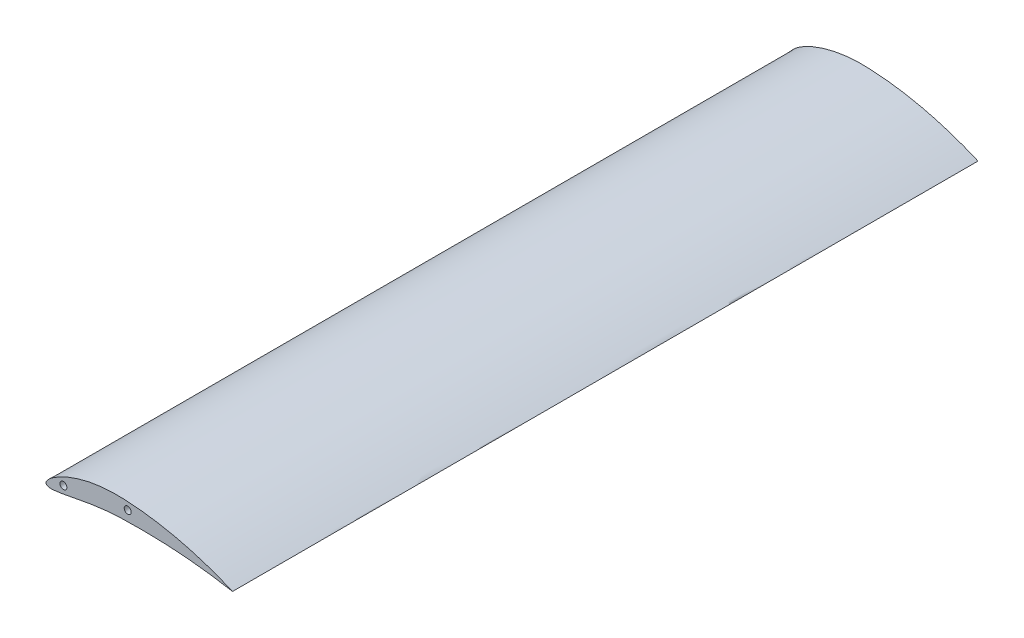
SolidWorks part; units mm, degrees
material "Thornel Mat VMA"
ref_plane "Front Plane" through (0, 0, 0) normal (0, 0, 1) x (1, 0, 0)
ref_plane "Top Plane" through (0, 0, 0) normal (0, 1, 0) x (1, 0, 0)
ref_plane "Right Plane" through (0, 0, 0) normal (1, 0, 0) x (0, 0, -1)
curve "Curve1"
  spline degree 3 poles (253.4485, 0.1124, 0) (254.1344, -0.0403, 0) (253.4775, 0.2094, 0) (252.9495, 0.4611, 0) (251.6343, 1.0083, 0) (250.0027, 1.7035, 0) (247.8318, 2.6061, 0) (245.222, 3.6772, 0) (242.1466, 4.9135, 0) (238.6277, 6.2968, 0) (234.6723, 7.8101, 0) (230.2949, 9.4358, 0) (225.5097, 11.1539, 0) (220.3329, 12.9444, 0) (214.7822, 14.7852, 0) (208.8774, 16.6562, 0) (202.6392, 18.5351, 0) (196.0902, 20.401, 0) (189.2544, 22.2326, 0) (182.1573, 24.0099, 0) (174.8257, 25.7128, 0) (167.2876, 27.3233, 0) (159.5723, 28.8237, 0) (151.7102, 30.1982, 0) (143.7328, 31.4322, 0) (135.6725, 32.5129, 0) (127.5623, 33.4286, 0) (119.4362, 34.1722, 0) (111.3283, 34.7326, 0) (103.2114, 35.1211, 0) (95.0995, 35.2824, 0) (87.0296, 35.0756, 0) (79.1065, 34.5435, 0) (71.3864, 33.6939, 0) (63.9086, 32.5516, 0) (56.7107, 31.1413, 0) (49.828, 29.4941, 0) (43.2936, 27.6424, 0) (37.1382, 25.6216, 0) (31.3885, 23.4707, 0) (26.0698, 21.2262, 0) (21.2028, 18.928, 0) (16.8058, 16.6139, 0) (12.8942, 14.3201, 0) (9.479, 12.0827, 0) (6.5699, 9.9326, 0) (4.1722, 7.8987, 0) (2.2877, 6.0051, 0) (0.9134, 4.2681, 0) (0.0444, 2.693, 0) (-0.3184, 1.2547, 0) (-0.0942, -0.0424, 0) (0.7257, -1.0686, 0) (2.0258, -1.7597, 0) (3.7478, -2.1864, 0) (5.9052, -2.3819, 0) (8.4963, -2.362, 0) (11.5132, -2.1403, 0) (14.9421, -1.7327, 0) (18.7667, -1.158, 0) (22.969, -0.4369, 0) (27.5301, 0.4071, 0) (32.4305, 1.3497, 0) (37.6504, 2.3649, 0) (43.1697, 3.4266, 0) (48.969, 4.507, 0) (55.0285, 5.5791, 0) (61.3291, 6.6157, 0) (67.8521, 7.5898, 0) (74.5787, 8.4752, 0) (81.4905, 9.2487, 0) (88.5689, 9.8833, 0) (95.8108, 10.3684, 0) (103.2588, 10.6511, 0) (110.8834, 10.8473, 0) (118.6426, 10.9921, 0) (126.4465, 11.0627, 0) (134.266, 11.0574, 0) (142.0724, 10.9714, 0) (149.836, 10.8029, 0) (157.5272, 10.5515, 0) (165.1159, 10.2196, 0) (172.5722, 9.8112, 0) (179.8661, 9.3312, 0) (186.9679, 8.7873, 0) (193.8486, 8.1886, 0) (200.4792, 7.5439, 0) (206.832, 6.8648, 0) (212.8796, 6.1626, 0) (218.596, 5.4497, 0) (223.9561, 4.7376, 0) (228.9365, 4.0391, 0) (233.5145, 3.366, 0) (237.67, 2.7297, 0) (241.3824, 2.1406, 0) (244.6389, 1.6085, 0) (247.4122, 1.1449, 0) (249.7238, 0.7475, 0) (251.4697, 0.4504, 0) (252.8691, 0.191, 0) (253.4485, 0.1124, 0) (254.1344, -0.0403, 0) (253.4775, 0.2094, 0) knots -0.004489 -0.002 -0.000501 0 0.0005 0.002 0.004491 0.007963 0.0124 0.017783 0.024086 0.031283 0.039342 0.048229 0.057904 0.068328 0.079457 0.091243 0.10364 0.116598 0.130063 0.143985 0.158306 0.172972 0.187927 0.203113 0.218472 0.233945 0.249473 0.264999 0.280462 0.295804 0.311324 0.326707 0.34181 0.356583 0.370972 0.384924 0.398387 0.411307 0.423633 0.435312 0.446295 0.456535 0.465988 0.474613 0.482377 0.489253 0.495224 0.500286 0.504461 0.507812 0.510481 0.512762 0.515043 0.517702 0.521013 0.525104 0.530021 0.535772 0.542341 0.549703 0.557819 0.566648 0.576147 0.586268 0.596965 0.60819 0.619899 0.632047 0.644592 0.657497 0.670724 0.68424 0.698011 0.712098 0.726728 0.741494 0.756341 0.771219 0.786073 0.800848 0.81549 0.829943 0.844153 0.858061 0.871615 0.884758 0.897436 0.909595 0.921182 0.932145 0.942437 0.952008 0.960816 0.968817 0.975974 0.98225 0.987616 0.992043 0.995511 0.998 0.999499 1 1.0005 1.002 1.004491 periodic
sketch "Sketch1" plane through (0, 0, 0) normal (0, 0, 1) x (1, 0, 0)
  spline S0 degree 3 poles (253.4485, 0.1124) (254.1344, -0.0403) (253.4775, 0.2094) (252.9495, 0.4611) (251.6343, 1.0083) (250.0027, 1.7035) (247.8318, 2.6061) (245.222, 3.6772) (242.1466, 4.9135) (238.6277, 6.2968) (234.6723, 7.8101) (230.2949, 9.4358) (225.5097, 11.1539) (220.3329, 12.9444) (214.7822, 14.7852) (208.8774, 16.6562) (202.6392, 18.5351) (196.0902, 20.401) (189.2544, 22.2326) (182.1573, 24.0099) (174.8257, 25.7128) (167.2876, 27.3233) (159.5723, 28.8237) (151.7102, 30.1982) (143.7328, 31.4322) (135.6725, 32.5129) (127.5623, 33.4286) (119.4362, 34.1722) (111.3283, 34.7326) (103.2114, 35.1211) (95.0995, 35.2824) (87.0296, 35.0756) (79.1065, 34.5435) (71.3864, 33.6939) (63.9086, 32.5516) (56.7107, 31.1413) (49.828, 29.4941) (43.2936, 27.6424) (37.1382, 25.6216) (31.3885, 23.4707) (26.0698, 21.2262) (21.2028, 18.928) (16.8058, 16.6139) (12.8942, 14.3201) (9.479, 12.0827) (6.5699, 9.9326) (4.1722, 7.8987) (2.2877, 6.0051) (0.9134, 4.2681) (0.0444, 2.693) (-0.3184, 1.2547) (-0.0942, -0.0424) (0.7257, -1.0686) (2.0258, -1.7597) (3.7478, -2.1864) (5.9052, -2.3819) (8.4963, -2.362) (11.5132, -2.1403) (14.9421, -1.7327) (18.7667, -1.158) (22.969, -0.4369) (27.5301, 0.4071) (32.4305, 1.3497) (37.6504, 2.3649) (43.1697, 3.4266) (48.969, 4.507) (55.0285, 5.5791) (61.3291, 6.6157) (67.8521, 7.5898) (74.5787, 8.4752) (81.4905, 9.2487) (88.5689, 9.8833) (95.8108, 10.3684) (103.2588, 10.6511) (110.8834, 10.8473) (118.6426, 10.9921) (126.4465, 11.0627) (134.266, 11.0574) (142.0724, 10.9714) (149.836, 10.8029) (157.5272, 10.5515) (165.1159, 10.2196) (172.5722, 9.8112) (179.8661, 9.3312) (186.9679, 8.7873) (193.8486, 8.1886) (200.4792, 7.5439) (206.832, 6.8648) (212.8796, 6.1626) (218.596, 5.4497) (223.9561, 4.7376) (228.9365, 4.0391) (233.5145, 3.366) (237.67, 2.7297) (241.3824, 2.1406) (244.6389, 1.6085) (247.4122, 1.1449) (249.7238, 0.7475) (251.4697, 0.4504) (252.8691, 0.191) (253.4485, 0.1124) (254.1344, -0.0403) (253.4775, 0.2094) knots -0.004489 -0.002 -0.000501 0 0.0005 0.002 0.004491 0.007963 0.0124 0.017783 0.024086 0.031283 0.039342 0.048229 0.057904 0.068328 0.079457 0.091243 0.10364 0.116598 0.130063 0.143985 0.158306 0.172972 0.187927 0.203113 0.218472 0.233945 0.249473 0.264999 0.280462 0.295804 0.311324 0.326707 0.34181 0.356583 0.370972 0.384924 0.398387 0.411307 0.423633 0.435312 0.446295 0.456535 0.465988 0.474613 0.482377 0.489253 0.495224 0.500286 0.504461 0.507812 0.510481 0.512762 0.515043 0.517702 0.521013 0.525104 0.530021 0.535772 0.542341 0.549703 0.557819 0.566648 0.576147 0.586268 0.596965 0.60819 0.619899 0.632047 0.644592 0.657497 0.670724 0.68424 0.698011 0.712098 0.726728 0.741494 0.756341 0.771219 0.786073 0.800848 0.81549 0.829943 0.844153 0.858061 0.871615 0.884758 0.897436 0.909595 0.921182 0.932145 0.942437 0.952008 0.960816 0.968817 0.975974 0.98225 0.987616 0.992043 0.995511 0.998 0.999499 1 1.0005 1.002 1.004491 only from (254, 0) to (254, 0) construction
  spline S1 degree 3 poles (253.4485, 0.1124) (254.1344, -0.0403) (253.4775, 0.2094) (252.9495, 0.4611) (251.6343, 1.0083) (250.0027, 1.7035) (247.8318, 2.6061) (245.222, 3.6772) (242.1466, 4.9135) (238.6277, 6.2968) (234.6723, 7.8101) (230.2949, 9.4358) (225.5097, 11.1539) (220.3329, 12.9444) (214.7822, 14.7852) (208.8774, 16.6562) (202.6392, 18.5351) (196.0902, 20.401) (189.2544, 22.2326) (182.1573, 24.0099) (174.8257, 25.7128) (167.2876, 27.3233) (159.5723, 28.8237) (151.7102, 30.1982) (143.7328, 31.4322) (135.6725, 32.5129) (127.5623, 33.4286) (119.4362, 34.1722) (111.3283, 34.7326) (103.2114, 35.1211) (95.0995, 35.2824) (87.0296, 35.0756) (79.1065, 34.5435) (71.3864, 33.6939) (63.9086, 32.5516) (56.7107, 31.1413) (49.828, 29.4941) (43.2936, 27.6424) (37.1382, 25.6216) (31.3885, 23.4707) (26.0698, 21.2262) (21.2028, 18.928) (16.8058, 16.6139) (12.8942, 14.3201) (9.479, 12.0827) (6.5699, 9.9326) (4.1722, 7.8987) (2.2877, 6.0051) (0.9134, 4.2681) (0.0444, 2.693) (-0.3184, 1.2547) (-0.0942, -0.0424) (0.7257, -1.0686) (2.0258, -1.7597) (3.7478, -2.1864) (5.9052, -2.3819) (8.4963, -2.362) (11.5132, -2.1403) (14.9421, -1.7327) (18.7667, -1.158) (22.969, -0.4369) (27.5301, 0.4071) (32.4305, 1.3497) (37.6504, 2.3649) (43.1697, 3.4266) (48.969, 4.507) (55.0285, 5.5791) (61.3291, 6.6157) (67.8521, 7.5898) (74.5787, 8.4752) (81.4905, 9.2487) (88.5689, 9.8833) (95.8108, 10.3684) (103.2588, 10.6511) (110.8834, 10.8473) (118.6426, 10.9921) (126.4465, 11.0627) (134.266, 11.0574) (142.0724, 10.9714) (149.836, 10.8029) (157.5272, 10.5515) (165.1159, 10.2196) (172.5722, 9.8112) (179.8661, 9.3312) (186.9679, 8.7873) (193.8486, 8.1886) (200.4792, 7.5439) (206.832, 6.8648) (212.8796, 6.1626) (218.596, 5.4497) (223.9561, 4.7376) (228.9365, 4.0391) (233.5145, 3.366) (237.67, 2.7297) (241.3824, 2.1406) (244.6389, 1.6085) (247.4122, 1.1449) (249.7238, 0.7475) (251.4697, 0.4504) (252.8691, 0.191) (253.4485, 0.1124) (254.1344, -0.0403) (253.4775, 0.2094) knots -0.004489 -0.002 -0.000501 0 0.0005 0.002 0.004491 0.007963 0.0124 0.017783 0.024086 0.031283 0.039342 0.048229 0.057904 0.068328 0.079457 0.091243 0.10364 0.116598 0.130063 0.143985 0.158306 0.172972 0.187927 0.203113 0.218472 0.233945 0.249473 0.264999 0.280462 0.295804 0.311324 0.326707 0.34181 0.356583 0.370972 0.384924 0.398387 0.411307 0.423633 0.435312 0.446295 0.456535 0.465988 0.474613 0.482377 0.489253 0.495224 0.500286 0.504461 0.507812 0.510481 0.512762 0.515043 0.517702 0.521013 0.525104 0.530021 0.535772 0.542341 0.549703 0.557819 0.566648 0.576147 0.586268 0.596965 0.60819 0.619899 0.632047 0.644592 0.657497 0.670724 0.68424 0.698011 0.712098 0.726728 0.741494 0.756341 0.771219 0.786073 0.800848 0.81549 0.829943 0.844153 0.858061 0.871615 0.884758 0.897436 0.909595 0.921182 0.932145 0.942437 0.952008 0.960816 0.968817 0.975974 0.98225 0.987616 0.992043 0.995511 0.998 0.999499 1 1.0005 1.002 1.004491 only from (254, 0) to (254, 0)
extrude "Boss-Extrude1" add sketch "Sketch1" along normal mid plane 1016
sketch "Sketch3" plane through (0, 0, -508) normal (0, 0, -1) x (-1, 0, 0)
  line L0 (-111.1224, 24.5559) -> (-23.4523, 9.8195) construction
  line L1 (-23.4523, 9.8195) -> (-23.4523, 19.9795) construction
  line L2 (-23.4523, 9.8195) -> (-23.4523, -0.3405) construction
  line L3 (-111.1224, 24.5559) -> (-111.1224, 34.7159) construction
  circle A0 centre (-23.4523, 9.8195) radius 4.7625
  circle A1 centre (-111.1224, 24.5559) radius 4.7625
  spline S1 degree 3 poles (-253.4775, 0.2094) (-254.1344, -0.0403) (-253.4485, 0.1124) (-252.8691, 0.191) (-251.4697, 0.4504) (-249.7238, 0.7475) (-247.4122, 1.1449) (-244.6389, 1.6085) (-241.3824, 2.1406) (-237.67, 2.7297) (-233.5145, 3.366) (-228.9365, 4.0391) (-223.9561, 4.7376) (-218.596, 5.4497) (-212.8796, 6.1626) (-206.832, 6.8648) (-200.4792, 7.5439) (-193.8486, 8.1886) (-186.9679, 8.7873) (-179.8661, 9.3312) (-172.5722, 9.8112) (-165.1159, 10.2196) (-157.5272, 10.5515) (-149.836, 10.8029) (-142.0724, 10.9714) (-134.266, 11.0574) (-126.4465, 11.0627) (-118.6426, 10.9921) (-110.8834, 10.8473) (-103.2588, 10.6511) (-95.8108, 10.3684) (-88.5689, 9.8833) (-81.4905, 9.2487) (-74.5787, 8.4752) (-67.8521, 7.5898) (-61.3291, 6.6157) (-55.0285, 5.5791) (-48.969, 4.507) (-43.1697, 3.4266) (-37.6504, 2.3649) (-32.4305, 1.3497) (-27.5301, 0.4071) (-22.969, -0.4369) (-18.7667, -1.158) (-14.9421, -1.7327) (-11.5132, -2.1403) (-8.4963, -2.362) (-5.9052, -2.3819) (-3.7478, -2.1864) (-2.0258, -1.7597) (-0.7257, -1.0686) (0.0942, -0.0424) (0.3184, 1.2547) (-0.0444, 2.693) (-0.9134, 4.2681) (-2.2877, 6.0051) (-4.1722, 7.8987) (-6.5699, 9.9326) (-9.479, 12.0827) (-12.8942, 14.3201) (-16.8058, 16.6139) (-21.2028, 18.928) (-26.0698, 21.2262) (-31.3885, 23.4707) (-37.1382, 25.6216) (-43.2936, 27.6424) (-49.828, 29.4941) (-56.7107, 31.1413) (-63.9086, 32.5516) (-71.3864, 33.6939) (-79.1065, 34.5435) (-87.0296, 35.0756) (-95.0995, 35.2824) (-103.2114, 35.1211) (-111.3283, 34.7326) (-119.4362, 34.1722) (-127.5623, 33.4286) (-135.6725, 32.5129) (-143.7328, 31.4322) (-151.7102, 30.1982) (-159.5723, 28.8237) (-167.2876, 27.3233) (-174.8257, 25.7128) (-182.1573, 24.0099) (-189.2544, 22.2326) (-196.0902, 20.401) (-202.6392, 18.5351) (-208.8774, 16.6562) (-214.7822, 14.7852) (-220.3329, 12.9444) (-225.5097, 11.1539) (-230.2949, 9.4358) (-234.6723, 7.8101) (-238.6277, 6.2968) (-242.1466, 4.9135) (-245.222, 3.6772) (-247.8318, 2.6061) (-250.0027, 1.7035) (-251.6343, 1.0083) (-252.9495, 0.4611) (-253.4775, 0.2094) (-254.1344, -0.0403) (-253.4485, 0.1124) knots -0.004491 -0.002 -0.0005 0 0.000501 0.002 0.004489 0.007957 0.012384 0.01775 0.024026 0.031183 0.039184 0.047992 0.057563 0.067855 0.078818 0.090405 0.102564 0.115242 0.128385 0.141939 0.155847 0.170057 0.18451 0.199152 0.213927 0.228781 0.243659 0.258506 0.273272 0.287902 0.301989 0.31576 0.329276 0.342503 0.355408 0.367953 0.380101 0.39181 0.403035 0.413732 0.423853 0.433352 0.442181 0.450297 0.457659 0.464228 0.469979 0.474896 0.478987 0.482298 0.484957 0.487238 0.489519 0.492188 0.495539 0.499714 0.504776 0.510747 0.517623 0.525387 0.534012 0.543465 0.553705 0.564688 0.576367 0.588693 0.601613 0.615076 0.629028 0.643417 0.65819 0.673293 0.688676 0.704196 0.719538 0.735001 0.750527 0.766055 0.781528 0.796887 0.812073 0.827028 0.841694 0.856015 0.869937 0.883402 0.89636 0.908757 0.920543 0.931672 0.942096 0.951771 0.960658 0.968717 0.975914 0.982217 0.9876 0.992037 0.995509 0.998 0.9995 1 1.000501 1.002 1.004489 only from (-254, 0) to (-254, 0) construction
  dimension "D1" = 9.525
  dimension "D2" = 10.16
  dimension "D5" = 9.525
  dimension "D3" = 10.16
  dimension "D4" = 10.16
  dimension "D6" = 88.9
extrude "Cut-Extrude1" cut sketch "Sketch3" against normal up to next
sketch "Sketch4" plane through (0, 0, 0) normal (0, 0, 1) x (1, 0, 0)
  line L0 (23.4523, 9.8195) -> (111.1224, 24.5559) construction
  line L1 (23.4523, 9.8195) -> (37.5007, -73.7576) construction
  line L2 (37.5007, -73.7576) -> (125.1709, -59.0212) construction
  line L3 (125.1709, -59.0212) -> (111.1224, 24.5559) construction
  line L4 (25.1094, -0.0388) -> (25.9515, -5.0485)
  line L5 (40.581, -15.4676) -> (103.2025, -4.9416)
  line L7 (113.6216, 9.6879) -> (113.4193, 10.8914)
  line L8 (39.1073, -6.7006) -> (89.2046, 1.7202) construction
  line L9 (40.581, -15.4676) -> (39.1073, -6.7006) construction
  arc A1 (25.9515, -5.0485) -> (40.581, -15.4676) centre (38.4758, -2.9433) ccw
  circle A2 centre (39.1073, -6.7006) radius 4.7625
  circle A3 centre (89.2046, 1.7202) radius 4.7625
  arc A6 (103.2025, -4.9416) -> (113.6216, 9.6879) centre (101.0973, 7.5827) ccw
  spline S0 degree 3 poles (253.4485, 0.1124) (254.1344, -0.0403) (253.4775, 0.2094) (252.9495, 0.4611) (251.6343, 1.0083) (250.0027, 1.7035) (247.8318, 2.6061) (245.222, 3.6772) (242.1466, 4.9135) (238.6277, 6.2968) (234.6723, 7.8101) (230.2949, 9.4358) (225.5097, 11.1539) (220.3329, 12.9444) (214.7822, 14.7852) (208.8774, 16.6562) (202.6392, 18.5351) (196.0902, 20.401) (189.2544, 22.2326) (182.1573, 24.0099) (174.8257, 25.7128) (167.2876, 27.3233) (159.5723, 28.8237) (151.7102, 30.1982) (143.7328, 31.4322) (135.6725, 32.5129) (127.5623, 33.4286) (119.4362, 34.1722) (111.3283, 34.7326) (103.2114, 35.1211) (95.0995, 35.2824) (87.0296, 35.0756) (79.1065, 34.5435) (71.3864, 33.6939) (63.9086, 32.5516) (56.7107, 31.1413) (49.828, 29.4941) (43.2936, 27.6424) (37.1382, 25.6216) (31.3885, 23.4707) (26.0698, 21.2262) (21.2028, 18.928) (16.8058, 16.6139) (12.8942, 14.3201) (9.479, 12.0827) (6.5699, 9.9326) (4.1722, 7.8987) (2.2877, 6.0051) (0.9134, 4.2681) (0.0444, 2.693) (-0.3184, 1.2547) (-0.0942, -0.0424) (0.7257, -1.0686) (2.0258, -1.7597) (3.7478, -2.1864) (5.9052, -2.3819) (8.4963, -2.362) (11.5132, -2.1403) (14.9421, -1.7327) (18.7667, -1.158) (22.969, -0.4369) (27.5301, 0.4071) (32.4305, 1.3497) (37.6504, 2.3649) (43.1697, 3.4266) (48.969, 4.507) (55.0285, 5.5791) (61.3291, 6.6157) (67.8521, 7.5898) (74.5787, 8.4752) (81.4905, 9.2487) (88.5689, 9.8833) (95.8108, 10.3684) (103.2588, 10.6511) (110.8834, 10.8473) (118.6426, 10.9921) (126.4465, 11.0627) (134.266, 11.0574) (142.0724, 10.9714) (149.836, 10.8029) (157.5272, 10.5515) (165.1159, 10.2196) (172.5722, 9.8112) (179.8661, 9.3312) (186.9679, 8.7873) (193.8486, 8.1886) (200.4792, 7.5439) (206.832, 6.8648) (212.8796, 6.1626) (218.596, 5.4497) (223.9561, 4.7376) (228.9365, 4.0391) (233.5145, 3.366) (237.67, 2.7297) (241.3824, 2.1406) (244.6389, 1.6085) (247.4122, 1.1449) (249.7238, 0.7475) (251.4697, 0.4504) (252.8691, 0.191) (253.4485, 0.1124) (254.1344, -0.0403) (253.4775, 0.2094) knots -0.004489 -0.002 -0.000501 0 0.0005 0.002 0.004491 0.007963 0.0124 0.017783 0.024086 0.031283 0.039342 0.048229 0.057904 0.068328 0.079457 0.091243 0.10364 0.116598 0.130063 0.143985 0.158306 0.172972 0.187927 0.203113 0.218472 0.233945 0.249473 0.264999 0.280462 0.295804 0.311324 0.326707 0.34181 0.356583 0.370972 0.384924 0.398387 0.411307 0.423633 0.435312 0.446295 0.456535 0.465988 0.474613 0.482377 0.489253 0.495224 0.500286 0.504461 0.507812 0.510481 0.512762 0.515043 0.517702 0.521013 0.525104 0.530021 0.535772 0.542341 0.549703 0.557819 0.566648 0.576147 0.586268 0.596965 0.60819 0.619899 0.632047 0.644592 0.657497 0.670724 0.68424 0.698011 0.712098 0.726728 0.741494 0.756341 0.771219 0.786073 0.800848 0.81549 0.829943 0.844153 0.858061 0.871615 0.884758 0.897436 0.909595 0.921182 0.932145 0.942437 0.952008 0.960816 0.968817 0.975974 0.98225 0.987616 0.992043 0.995511 0.998 0.999499 1 1.0005 1.002 1.004491 only from (254, 0) to (254, 0) construction
  spline S1 degree 3 poles (25.1094, -0.0388) (25.8778, 0.1027) (28.2837, 0.552) (32.4305, 1.3497) (37.6504, 2.3649) (43.1697, 3.4266) (48.969, 4.507) (55.0285, 5.5791) (61.3291, 6.6157) (67.8521, 7.5898) (74.5787, 8.4752) (81.4905, 9.2487) (88.5689, 9.8833) (95.8108, 10.3684) (103.2588, 10.6511) (109.1474, 10.8026) (112.5661, 10.8746) (113.4193, 10.8914) knots 0.562194 0.562194 0.562194 0.562194 0.566648 0.576147 0.586268 0.596965 0.60819 0.619899 0.632047 0.644592 0.657497 0.670724 0.68424 0.698011 0.712098 0.726728 0.731593 0.731593 0.731593 0.731593
  point P13 (115.7268, -2.8364)
  point P16 (28.0567, -17.5728)
  dimension "D2" = 8.89
  dimension "D4" = 12.7
  dimension "D5" = 9.525
  dimension "D6" = 50.8
  dimension "D7" = 9.525
  dimension "D1" = 12.7
  dimension "D3" = 17.78
extrude "Boss-Extrude2" add sketch "Sketch4" along normal mid plane 254
sketch "Sketch6" plane through (0, 0, 0) normal (0, 0, 1) x (1, 0, 0)
  line L3 (25.1094, -0.0388) -> (25.9515, -5.0485)
  line L4 (40.581, -15.4676) -> (103.2025, -4.9416)
  line L5 (113.6216, 9.6879) -> (113.4193, 10.8914)
  line L6 (25.1094, -0.0388) -> (25.9515, -5.0485)
  line L7 (40.581, -15.4676) -> (103.2025, -4.9416)
  line L8 (113.6216, 9.6879) -> (113.4193, 10.8914)
  arc A2 (25.9515, -5.0485) -> (40.581, -15.4676) centre (38.4758, -2.9433) ccw
  arc A3 (103.2025, -4.9416) -> (113.6216, 9.6879) centre (101.0973, 7.5827) ccw
  arc A4 (25.9515, -5.0485) -> (40.581, -15.4676) centre (38.4758, -2.9433) ccw
  arc A5 (103.2025, -4.9416) -> (113.6216, 9.6879) centre (101.0973, 7.5827) ccw
  spline S1 degree 3 poles (805.3324, -2857.0033) (599.1623, -59.5557) (351.4394, 17.0385) (103.2588, 10.6511) (95.8108, 10.3684) (88.5689, 9.8833) (81.4905, 9.2487) (74.5787, 8.4752) (67.8521, 7.5898) (61.3291, 6.6157) (55.0285, 5.5791) (48.969, 4.507) (43.1697, 3.4266) (37.6504, 2.3649) (32.4305, 1.3497) (-95.4028, -23.2393) (-228.2762, -11.8851) (-847.6223, 2855.8169) knots -1.113377 -1.113377 -1.113377 -1.113377 0.273272 0.287902 0.301989 0.31576 0.329276 0.342503 0.355408 0.367953 0.380101 0.39181 0.403035 0.413732 0.423853 0.433352 1.155877 1.155877 1.155877 1.155877 only from (113.4193, 10.8914) to (25.1094, -0.0388)
  spline S2 degree 3 poles (113.4193, 10.8914) (112.5661, 10.8746) (109.1474, 10.8026) (103.2588, 10.6511) (95.8108, 10.3684) (88.5689, 9.8833) (81.4905, 9.2487) (74.5787, 8.4752) (67.8521, 7.5898) (61.3291, 6.6157) (55.0285, 5.5791) (48.969, 4.507) (43.1697, 3.4266) (37.6504, 2.3649) (32.4305, 1.3497) (28.2837, 0.552) (25.8778, 0.1027) (25.1094, -0.0388) knots 0.268407 0.268407 0.268407 0.268407 0.273272 0.287902 0.301989 0.31576 0.329276 0.342503 0.355408 0.367953 0.380101 0.39181 0.403035 0.413732 0.423853 0.433352 0.437806 0.437806 0.437806 0.437806
  dimension "D1" = 0
extrude "Cut-Extrude3" cut sketch "Sketch6" against normal mid plane 241.3
